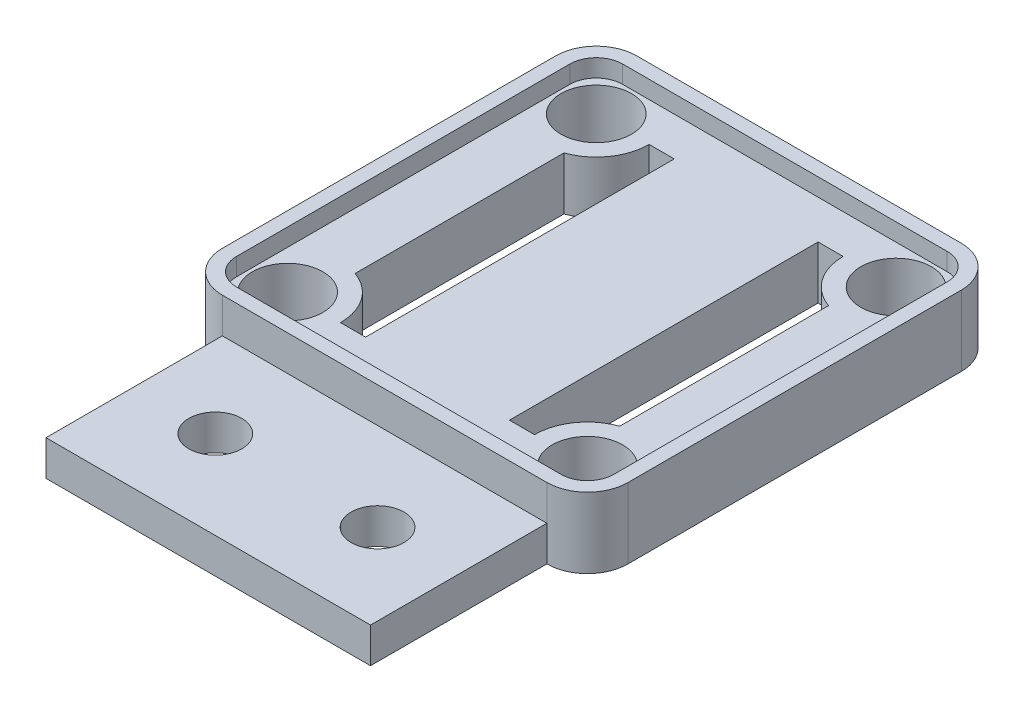
SolidWorks part; units mm, degrees
ref_plane "Front Plane" through (0, 0, 0) normal (0, 0, 1) x (1, 0, 0)
ref_plane "Top Plane" through (0, 0, 0) normal (0, 1, 0) x (1, 0, 0)
ref_plane "Right Plane" through (0, 0, 0) normal (1, 0, 0) x (0, 0, -1)
sketch "Sketch1" plane through (0, 0, 0) normal (0, 1, 0) x (1, 0, 0)
  line L1 (-12.6491, 14.6331) -> (5.7509, 14.6331)
  line L2 (-14.9491, 12.3331) -> (-14.9491, -6.5669)
  line L3 (-12.6491, -8.8669) -> (5.7509, -8.8669)
  line L4 (8.0509, 12.3331) -> (8.0509, -6.5669)
  line L5 (-14.9491, 14.6331) -> (8.0509, -8.8669) construction
  line L6 (-14.9491, -8.8669) -> (8.0509, 14.6331) construction
  arc A0 (8.0509, 12.3331) -> (5.7509, 14.6331) centre (5.7509, 12.3331) ccw
  arc A1 (-12.6491, -8.8669) -> (-14.9491, -6.5669) centre (-12.6491, -6.5669) cw
  arc A2 (5.7509, -8.8669) -> (8.0509, -6.5669) centre (5.7509, -6.5669) ccw
  arc A3 (-14.9491, 12.3331) -> (-12.6491, 14.6331) centre (-12.6491, 12.3331) cw
  point P0 (-3.4491, 2.8831)
  dimension "D3" = 2.3
  dimension "D4" = 2.3
  dimension "D1" = 23.5
  dimension "D2" = 23
extrude "Boss-Extrude1" add sketch "Sketch1" along normal blind 4
sketch "Sketch2" plane through (0, 4, 0) normal (0, 1, 0) x (1, 0, 0)
  line L8 (5.7509, 13.6331) -> (-12.6491, 13.6331)
  line L9 (-13.9491, 12.3331) -> (-13.9491, -6.5669)
  line L10 (-12.6491, -7.8669) -> (5.7509, -7.8669)
  line L11 (7.0509, -6.5669) -> (7.0509, 12.3331)
  line L12 (5.7509, 13.6331) -> (-12.6491, 13.6331)
  line L13 (-13.9491, 12.3331) -> (-13.9491, -6.5669)
  line L14 (-12.6491, -7.8669) -> (5.7509, -7.8669)
  line L15 (7.0509, -6.5669) -> (7.0509, 12.3331)
  arc A8 (7.0509, 12.3331) -> (5.7509, 13.6331) centre (5.7509, 12.3331) ccw
  arc A9 (-12.6491, 13.6331) -> (-13.9491, 12.3331) centre (-12.6491, 12.3331) ccw
  arc A10 (-13.9491, -6.5669) -> (-12.6491, -7.8669) centre (-12.6491, -6.5669) ccw
  arc A11 (5.7509, -7.8669) -> (7.0509, -6.5669) centre (5.7509, -6.5669) ccw
  arc A12 (7.0509, 12.3331) -> (5.7509, 13.6331) centre (5.7509, 12.3331) ccw
  arc A13 (-12.6491, 13.6331) -> (-13.9491, 12.3331) centre (-12.6491, 12.3331) ccw
  arc A14 (-13.9491, -6.5669) -> (-12.6491, -7.8669) centre (-12.6491, -6.5669) ccw
  arc A15 (5.7509, -7.8669) -> (7.0509, -6.5669) centre (5.7509, -6.5669) ccw
  dimension "D1" = 1
extrude "Cut-Extrude2" cut sketch "Sketch2" against normal blind 1
sketch "Sketch5" plane through (0, 3, 0) normal (0, 1, 0) x (1, 0, 0)
  line L0 (-3.4491, 13.6331) -> (-3.4491, -7.8669) construction
  line L1 (5.7509, 13.6331) -> (-12.6491, 13.6331) construction
  line L2 (-12.6491, -7.8669) -> (5.7509, -7.8669) construction
  line L3 (7.0509, 2.8831) -> (-13.9491, 2.8831) construction
  line L4 (7.0509, -6.5669) -> (7.0509, 12.3331) construction
  line L5 (-13.9491, 12.3331) -> (-13.9491, -6.5669) construction
  circle A0 centre (5.0509, 11.6331) radius 2
  circle A1 centre (5.0509, -5.8669) radius 2
  circle A2 centre (-11.9491, -5.8669) radius 2
  circle A3 centre (-11.9491, 11.6331) radius 2
  dimension "D1" = 4
extrude "Cut-Extrude3" cut sketch "Sketch5" against normal through all
sketch "Sketch6" plane through (0, 3, 0) normal (0, 1, 0) x (1, 0, 0)
  line L0 (-14.9491, 12.3331) -> (-14.9491, -6.5669) construction
  line L1 (8.0509, -6.5669) -> (8.0509, 12.3331) construction
  line L14 (4.0509, -5.8669) -> (4.0509, 11.6331)
  line L15 (4.0509, -3.0385) -> (4.0509, 8.8047)
  line L16 (2.0509, 11.6331) -> (2.0509, -5.8669)
  line L17 (-10.9491, 12.3331) -> (-10.9491, -6.5669)
  line L18 (-10.9491, 8.8047) -> (-10.9491, -3.0385)
  line L19 (-8.9491, 11.6331) -> (-8.9491, -5.8669)
  arc A5 (-11.9491, -8.8669) -> (-14.9491, -5.8669) centre (-11.9491, -5.8669) ccw
  arc A6 (-8.9491, -5.8669) -> (-10.9491, -3.0385) centre (-11.9491, -5.8669) ccw
  arc A20 (5.0509, 14.6331) -> (8.0509, 11.6331) centre (5.0509, 11.6331) ccw
  arc A21 (2.0509, 11.6331) -> (4.0509, 8.8047) centre (5.0509, 11.6331) ccw
  arc A23 (-14.9491, 11.6331) -> (-11.9491, 14.6331) centre (-11.9491, 11.6331) ccw
  arc A24 (-10.9491, 8.8047) -> (-8.9491, 11.6331) centre (-11.9491, 11.6331) ccw
  arc A26 (8.0509, -5.8669) -> (5.0509, -8.8669) centre (5.0509, -5.8669) ccw
  arc A27 (4.0509, -3.0385) -> (2.0509, -5.8669) centre (5.0509, -5.8669) ccw
  dimension "D1" = 23
  dimension "D2" = 1
  dimension "D3" = 1
  dimension "D4" = 1
  dimension "D5" = 1
  dimension "D6" = 3
  dimension "D7" = 3
extrude "Cut-Extrude4" cut sketch "Sketch6" against normal through all
sketch "Sketch7" plane through (0, 0, 8.8669) normal (0, 0, 1) x (1, 0, 0)
  line L0 (-14.9491, 4) -> (-14.9491, 0) construction
  line L1 (8.0509, 4) -> (8.0509, 0) construction
  line L2 (-12.6491, 4) -> (-12.6491, 0) construction
  line L3 (-12.6491, 2) -> (5.7509, 2)
  line L4 (5.7509, 4) -> (5.7509, 0) construction
  line L5 (5.7509, 2) -> (5.7509, 0)
  line L6 (5.7509, 0) -> (-12.6491, 0)
  line L7 (-12.6491, 0) -> (-12.6491, 2)
  dimension "D1" = 23
extrude "Boss-Extrude2" add sketch "Sketch7" along normal blind 10
sketch "Sketch8" plane through (0, 2, 0) normal (0, 1, 0) x (1, 0, 0)
  line L0 (-12.6491, -8.8669) -> (5.7509, -8.8669) construction
  line L1 (-12.6491, -18.8669) -> (-12.6491, -8.8669) construction
  line L2 (5.7509, -18.8669) -> (5.7509, -8.8669) construction
  line L3 (-3.4491, -8.8669) -> (-3.4491, -18.8669) construction
  line L4 (5.7509, -18.8669) -> (-12.6491, -18.8669) construction
  circle A0 centre (1.1509, -13.8669) radius 1.5
  circle A1 centre (-8.0491, -13.8669) radius 1.5
  dimension "D2" = 3
  dimension "D1" = 5
  dimension "D3" = 18.4
  dimension "D4" = 4.6
  dimension "D5" = 4.6
extrude "Cut-Extrude5" cut sketch "Sketch8" against normal through all
sketch "Sketch9" plane through (0, 4, 0) normal (0, 1, 0) x (1, 0, 0)
  line L8 (5.7509, 13.8331) -> (-12.6491, 13.8331)
  line L9 (-14.1491, 12.3331) -> (-14.1491, -6.5669)
  line L10 (-12.6491, -8.0669) -> (5.7509, -8.0669)
  line L11 (7.2509, -6.5669) -> (7.2509, 12.3331)
  line L12 (5.7509, 13.8331) -> (-12.6491, 13.8331)
  line L13 (-14.1491, 12.3331) -> (-14.1491, -6.5669)
  line L14 (-12.6491, -8.0669) -> (5.7509, -8.0669)
  line L15 (7.2509, -6.5669) -> (7.2509, 12.3331)
  arc A8 (7.2509, 12.3331) -> (5.7509, 13.8331) centre (5.7509, 12.3331) ccw
  arc A9 (-12.6491, 13.8331) -> (-14.1491, 12.3331) centre (-12.6491, 12.3331) ccw
  arc A10 (-14.1491, -6.5669) -> (-12.6491, -8.0669) centre (-12.6491, -6.5669) ccw
  arc A11 (5.7509, -8.0669) -> (7.2509, -6.5669) centre (5.7509, -6.5669) ccw
  arc A12 (7.2509, 12.3331) -> (5.7509, 13.8331) centre (5.7509, 12.3331) ccw
  arc A13 (-12.6491, 13.8331) -> (-14.1491, 12.3331) centre (-12.6491, 12.3331) ccw
  arc A14 (-14.1491, -6.5669) -> (-12.6491, -8.0669) centre (-12.6491, -6.5669) ccw
  arc A15 (5.7509, -8.0669) -> (7.2509, -6.5669) centre (5.7509, -6.5669) ccw
  dimension "D1" = 0.8
extrude "Cut-Extrude6" cut sketch "Sketch9" against normal blind 1
sketch "Sketch11" plane through (0, 3, 0) normal (0, 1, 0) x (1, 0, 0)
  line L0 (-8.9491, 11.6331) -> (-7.528, 11.6331)
  line L1 (-7.528, 11.6331) -> (-7.528, -5.8669)
  line L2 (-7.528, -5.8669) -> (-8.9491, -5.8669)
  line L3 (-8.9491, -5.8669) -> (-8.9491, 11.6331)
  line L4 (-3.4491, 13.8331) -> (-3.4491, -8.0669) construction
  line L5 (5.7509, 13.8331) -> (-12.6491, 13.8331) construction
  line L6 (-12.6491, -8.0669) -> (5.7509, -8.0669) construction
  line L7 (0.6299, -5.8669) -> (2.0509, -5.8669)
  line L8 (0.6299, 11.6331) -> (0.6299, -5.8669)
  line L9 (2.0509, 11.6331) -> (0.6299, 11.6331)
  line L10 (2.0509, -5.8669) -> (2.0509, 11.6331)
extrude "Cut-Extrude7" cut sketch "Sketch11" against normal through all
